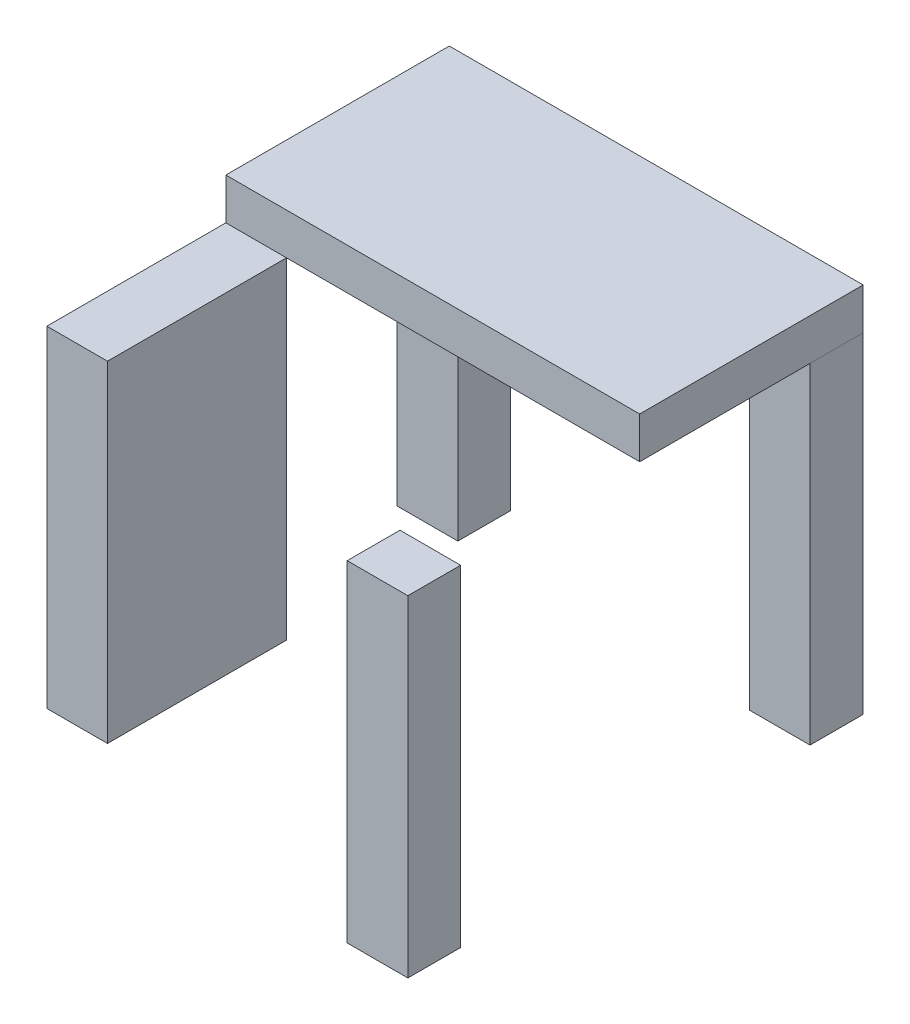
SolidWorks part; units mm, degrees
ref_plane "Front Plane" through (0, 0, 0) normal (0, 0, 1) x (1, 0, 0)
ref_plane "Top Plane" through (0, 0, 0) normal (0, 1, 0) x (1, 0, 0)
ref_plane "Right Plane" through (0, 0, 0) normal (1, 0, 0) x (0, 0, -1)
sketch "Sketch1" plane through (0, 0, 0) normal (0, 0, 1) x (1, 0, 0)
  line L1 (0, 0) -> (100, 0)
  line L2 (0, 0) -> (0, 10)
  line L3 (0, 10) -> (100, 10)
  line L4 (100, 0) -> (100, 10)
  dimension "D1" = 10
  dimension "D2" = 100
extrude "Boss-Extrude1" add sketch "Sketch1" along normal blind 54
sketch "Sketch2" plane through (0, 0, 0) normal (0, -1, 0) x (1, 0, 0)
  line L0 (85.3618, 110.0347) -> (100.0191, 110.0347)
  line L1 (0, 54) -> (14.6573, 54)
  line L2 (0, 54) -> (0, 97.2496)
  line L3 (0, 97.2496) -> (14.6573, 97.2496)
  line L4 (14.6573, 54) -> (14.6573, 97.2496)
  line L5 (85.3618, 110.0347) -> (85.3618, 97.2843)
  line L6 (85.3618, 97.2843) -> (100.0191, 97.2843)
  line L7 (100.0191, 110.0347) -> (100.0191, 97.2843)
  line L8 (-0.0191, 12.5688) -> (14.6382, 12.5688)
  line L9 (-0.0191, 12.5688) -> (-0.0191, -0.1816)
  line L10 (-0.0191, -0.1816) -> (14.6382, -0.1816)
  line L11 (14.6382, 12.5688) -> (14.6382, -0.1816)
  line L12 (85.2149, 12.7157) -> (99.8722, 12.7157)
  line L13 (85.2149, 12.7157) -> (85.2149, -0.0347)
  line L14 (85.2149, -0.0347) -> (99.8722, -0.0347)
  line L15 (99.8722, 12.7157) -> (99.8722, -0.0347)
extrude "Boss-Extrude2" add sketch "Sketch2" along normal blind 80
equation "\"LTest\" = 54mm"
equation "\"D1@Boss-Extrude1\"=\"LTest\""
